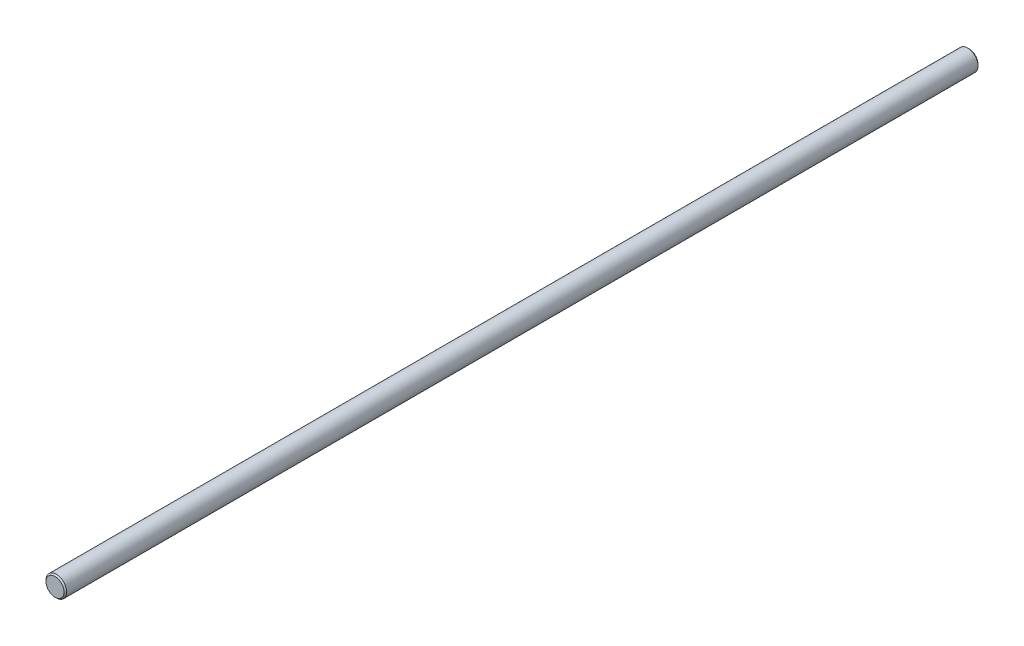
SolidWorks part; units mm, degrees
ref_plane "Front Plane" through (0, 0, 0) normal (0, 0, 1) x (1, 0, 0)
ref_plane "Top Plane" through (0, 0, 0) normal (0, 1, 0) x (1, 0, 0)
ref_plane "Right Plane" through (0, 0, 0) normal (1, 0, 0) x (0, 0, -1)
ref_plane "Plane1" through (0, 0, 0) normal (0, -1, 0) x (1, 0, 0)
sketch "Sketch1" plane through (0, 0, 0) normal (0, -1, 0) x (1, 0, 0)
  line L0 (3.5, 355) -> (0, 355)
  line L1 (0, 355) -> (0, 0)
  line L2 (0, 0) -> (3.5, 0)
  line L3 (3.5, 0) -> (4, 0.5)
  line L4 (4, 0.5) -> (4, 354.5)
  line L5 (4, 354.5) -> (3.5, 355)
  line L6 (0, 355) -> (0, 0) construction
revolve "Revolve1" add sketch "Sketch1" angle 360 about L6
